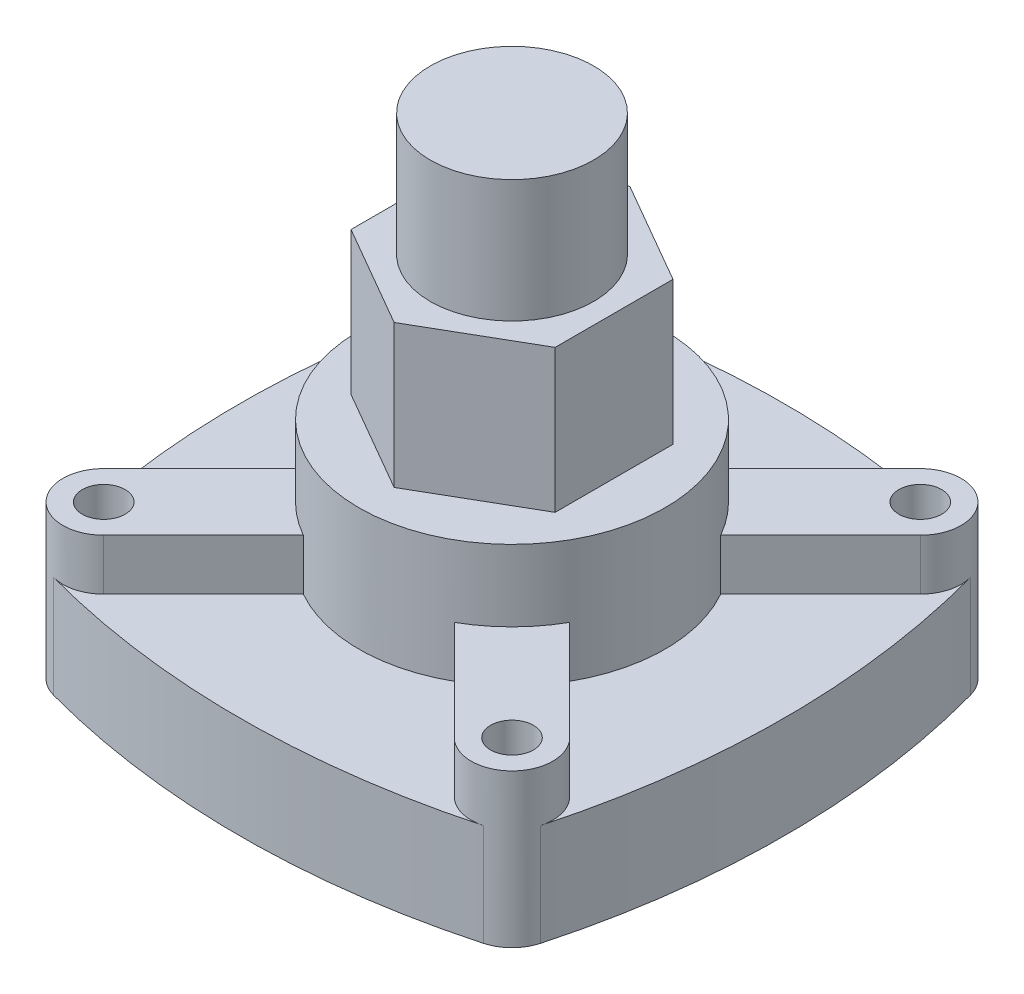
SolidWorks part; units mm, degrees
ref_plane "Front Plane" through (0, 0, 0) normal (0, 0, 1) x (1, 0, 0)
ref_plane "Top Plane" through (0, 0, 0) normal (0, 1, 0) x (1, 0, 0)
ref_plane "Right Plane" through (0, 0, 0) normal (1, 0, 0) x (0, 0, -1)
sketch "Sketch3" plane through (0, 0, 0) normal (0, 1, 0) x (1, 0, 0)
  line L0 (0, 0) -> (0, 10.5413) construction
  line L5 (-20, -20) -> (20, -20) construction
  line L6 (-20, -20) -> (-20, 20) construction
  line L7 (-20, 20) -> (20, 20) construction
  line L8 (20, -20) -> (20, 20) construction
  line L9 (-20, -20) -> (20, 20) construction
  line L10 (-20, 20) -> (20, -20) construction
  line L11 (0, 0) -> (14.8148, 0) construction
  line L12 (0, 0) -> (0, 26.6788) construction
  line L13 (0, 0) -> (26.6788, 0) construction
  line L14 (0, 0) -> (0, -26.6788) construction
  line L15 (0, 0) -> (-26.6788, 0) construction
  circle A0 centre (20, 20) radius 4
  circle A1 centre (20, -20) radius 4
  circle A2 centre (-20, -20) radius 4
  circle A3 centre (-20, 20) radius 4
  arc A4 (-21.0526, 23.859) -> (21.0526, 23.859) centre (0, -53.3212) cw
  arc A5 (23.859, 21.0526) -> (23.859, -21.0526) centre (-53.3212, 0) cw
  arc A6 (21.0526, -23.859) -> (-21.0526, -23.859) centre (0, 53.3212) cw
  arc A7 (-23.859, -21.0526) -> (-23.859, 21.0526) centre (53.3212, 0) cw
  point P0 (0, 0)
  point P32 (0, 0)
  dimension "D1" = 8
  dimension "D3" = 80
  dimension "D2" = 20
  dimension "D4" = 4
extrude "Boss-Extrude2" add sketch "Sketch3" along normal blind 10 contours A2 | A7 A2 A6 A1 A5 A0 A4 A3 | A3 | A1 | A0
sketch "Sketch4" plane through (0, 10, 0) normal (0, 1, 0) x (1, 0, 0)
  circle A0 centre (0, 0) radius 15
  dimension "D1" = 30
extrude "Boss-Extrude3" add sketch "Sketch4" along normal blind 12
shell "Shell2" thickness 1
sketch "Sketch5" plane through (0, 22, 0) normal (0, 1, 0) x (1, 0, 0)
  line L1 (0, 11.547) -> (-10, 5.7735)
  line L2 (-10, 5.7735) -> (-10, -5.7735)
  line L3 (-10, -5.7735) -> (0, -11.547)
  line L4 (0, -11.547) -> (10, -5.7735)
  line L5 (10, -5.7735) -> (10, 5.7735)
  line L6 (10, 5.7735) -> (0, 11.547)
  circle A0 centre (0, 0) radius 10 construction
  point P1 (0, 0)
  dimension "D1" = 20
extrude "Boss-Extrude4" add sketch "Sketch5" along normal blind 14
sketch "Sketch6" plane through (0, 36, 0) normal (0, 1, 0) x (1, 0, 0)
  circle A0 centre (0, 0) radius 8
extrude "Boss-Extrude5" add sketch "Sketch6" along normal blind 12
sketch "Sketch7" plane through (0, 10, 0) normal (0, 1, 0) x (1, 0, 0)
  line L0 (-17.1716, 22.8284) -> (-7.3941, 13.051)
  line L1 (0, 0) -> (-26.6788, 0) construction
  line L2 (-20, -20) -> (-20, 20) construction
  line L3 (-20, -20) -> (20, -20) construction
  line L4 (0, 0) -> (0, -26.6788) construction
  line L5 (0, 0) -> (26.6788, 0) construction
  line L6 (20, -20) -> (20, 20) construction
  line L7 (-20, -20) -> (20, 20) construction
  line L8 (-20, 20) -> (20, 20) construction
  line L9 (0, 0) -> (0, 26.6788) construction
  line L10 (-20, 20) -> (20, -20) construction
  line L11 (0, 0) -> (-26.6788, 0)
  line L12 (-20, -20) -> (-20, 20)
  line L13 (-20, -20) -> (20, -20)
  line L14 (0, 0) -> (0, -26.6788)
  line L15 (0, 0) -> (26.6788, 0)
  line L16 (20, -20) -> (20, 20)
  line L17 (-20, -20) -> (20, 20)
  line L18 (-20, 20) -> (20, 20)
  line L19 (0, 0) -> (0, 26.6788)
  line L20 (-20, 20) -> (20, -20)
  line L21 (0, 0) -> (-11.6029, 11.6029) construction
  line L22 (-22.8284, 17.1716) -> (-13.051, 7.3941)
  line L23 (22.8284, 17.1716) -> (13.051, 7.3941)
  line L24 (20, 20) -> (-20, -20)
  line L25 (17.1716, 22.8284) -> (7.3941, 13.051)
  line L26 (17.1716, -22.8284) -> (7.3941, -13.051)
  line L27 (20, -20) -> (-20, 20)
  line L28 (22.8284, -17.1716) -> (13.051, -7.3941)
  line L29 (-22.8284, -17.1716) -> (-13.051, -7.3941)
  line L30 (-20, -20) -> (20, 20)
  line L31 (-17.1716, -22.8284) -> (-7.3941, -13.051)
  circle A0 centre (-20, -20) radius 4 construction
  circle A1 centre (20, -20) radius 4 construction
  circle A2 centre (20, 20) radius 4 construction
  circle A3 centre (-20, 20) radius 4 construction
  circle A4 centre (-20, -20) radius 4
  circle A5 centre (20, -20) radius 4
  circle A6 centre (20, 20) radius 4
  circle A7 centre (-20, 20) radius 4
  arc A8 (-23.859, -21.0526) -> (-21.0526, -23.859) centre (-20, -20) ccw
  arc A9 (-21.0526, -23.859) -> (21.0526, -23.859) centre (0, 53.3212) ccw
  arc A10 (21.0526, -23.859) -> (23.859, -21.0526) centre (20, -20) ccw
  arc A11 (23.859, -21.0526) -> (23.859, 21.0526) centre (-53.3212, 0) ccw
  arc A12 (23.859, 21.0526) -> (21.0526, 23.859) centre (20, 20) ccw
  arc A13 (21.0526, 23.859) -> (-21.0526, 23.859) centre (0, -53.3212) ccw
  arc A14 (-21.0526, 23.859) -> (-23.859, 21.0526) centre (-20, 20) ccw
  arc A15 (-23.859, 21.0526) -> (-23.859, -21.0526) centre (53.3212, 0) ccw
  arc A16 (-23.859, -21.0526) -> (-21.0526, -23.859) centre (-20, -20) ccw
  arc A17 (-21.0526, -23.859) -> (21.0526, -23.859) centre (0, 53.3212) ccw
  arc A18 (21.0526, -23.859) -> (23.859, -21.0526) centre (20, -20) ccw
  arc A19 (23.859, -21.0526) -> (23.859, 21.0526) centre (-53.3212, 0) ccw
  arc A20 (23.859, 21.0526) -> (21.0526, 23.859) centre (20, 20) ccw
  arc A21 (21.0526, 23.859) -> (-21.0526, 23.859) centre (0, -53.3212) ccw
  arc A22 (-21.0526, 23.859) -> (-23.859, 21.0526) centre (-20, 20) ccw
  arc A23 (-23.859, 21.0526) -> (-23.859, -21.0526) centre (53.3212, 0) ccw
  circle A24 centre (0, 0) radius 15 construction
  circle A25 centre (0, 0) radius 15
  point P57 (0, 0)
  circle M12 centre (0, 0) radius 15
  arc M13 (-23.859, -21.0526) -> (-21.0526, -23.859) centre (-20, -20) ccw
  arc M15 (21.0526, -23.859) -> (23.859, -21.0526) centre (20, -20) ccw
  arc M17 (23.859, 21.0526) -> (21.0526, 23.859) centre (20, 20) ccw
  arc M19 (-21.0526, 23.859) -> (-23.859, 21.0526) centre (-20, 20) ccw
  dimension "D1" = 0
  dimension "D2" = 4
extrude "Boss-Extrude6" add sketch "Sketch7" along normal blind 5 contours L16 A6 L18 M17 | L18 A6 L30 | L30 A6 L16 | A6 L17 L23 L16 M12 | A6 L18 L25 L17 M12 | A4 L13 L31 L30 M12 | A4 L30 L29 L12 M12 | L13 A4 L17 | L17 A4 L12 | L12 A4 L13 M13 | A5 L16 L13 M15 | L27 A5 L13 | L16 A5 L27 | A5 L16 L28 L20 M12 | A5 L20 L26 L13 M12 | A6 L25 L18 | A6 L16 L23 | L18 A7 L12 M19 | A7 L22 L12 | L12 A7 L20 | L20 A7 L18 | A7 L18 L0 | A7 L27 L20 L0 L18 M12 | A7 L12 L22 L20 L27 M12 | A4 L31 L13 | A4 L12 L29 | A5 L13 L26 | A5 L28 L16
sketch "Sketch10" plane through (0, 15, 0) normal (0, 1, 0) x (1, 0, 0)
  point P0 (20, -20)
  point P3 (20, 20)
  point P6 (-20, 20)
  point P9 (-20, -20)
hole_wizard "M5x0.8 Tapped Hole1" positions "Sketch10" profile "Sketch9" tap size "M5x0.8" standard "ANSI Metric" end condition up to next
sketch "Sketch9" plane through (20, 15, 20) normal (1, 0, 0) x (0, 0, 1)
  line L0 (0, 0) -> (0, 6)
  line L1 (0, 6) -> (2.1, 6)
  line L2 (2.1, 6) -> (2.1, 0)
  line L5 (2.1, 0) -> (0, 0)
  line L11 (0, -6.35) -> (0, 107.95) construction
  dimension "Thru Tap Drill Dia." = 4.2
  dimension "Thru Tap Drill Depth" = 6
cosmetic thread "Hole Thread1" parameters "D2"=5
cosmetic thread "Hole Thread2" parameters "D2"=5
cosmetic thread "Hole Thread3" parameters "D2"=5
cosmetic thread "Hole Thread4" parameters "D2"=5
